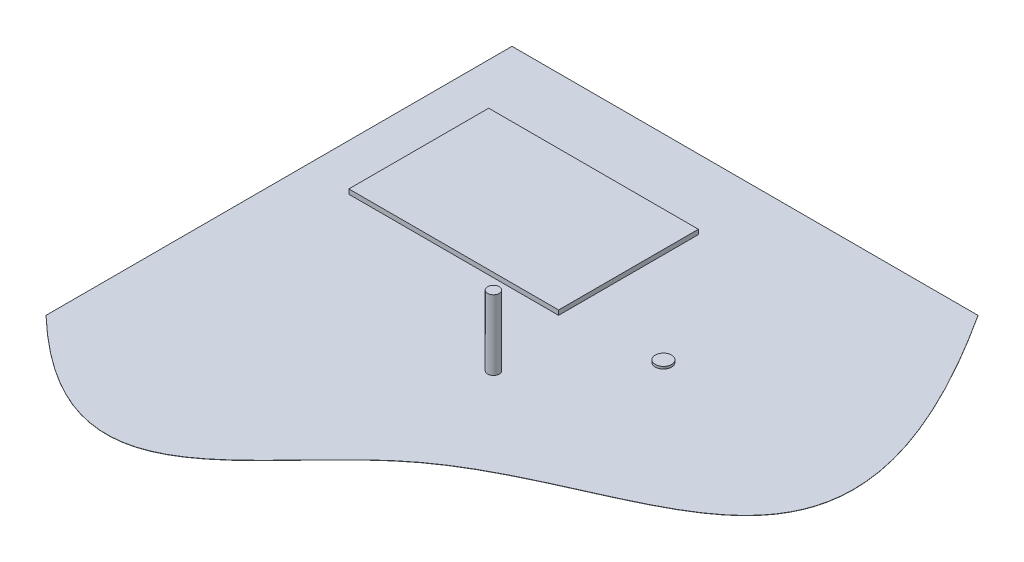
SolidWorks part; units mm, degrees
ref_plane "Спереди" through (0, 0, 0) normal (0, 0, 1) x (1, 0, 0)
ref_plane "Сверху" through (0, 0, 0) normal (0, 1, 0) x (1, 0, 0)
ref_plane "Справа" through (0, 0, 0) normal (1, 0, 0) x (0, 0, -1)
sketch "Эскиз1" plane through (0, 0, 0) normal (0, 1, 0) x (1, 0, 0)
  line L0 (0, 0) -> (20000, 0)
  line L1 (0, 0) -> (0, -20000)
  spline S0 degree 3 poles (0, -20000) (7198.3528, -26864.5196) (12070.5058, -12028.819) (29348.4021, -14440.6963) (20000, 0) knots 0 0 0 0 0.41356 1 1 1 1
  point P5 (8873.6019, -21813.3955)
  dimension "D1" = 20000
  dimension "D2" = 20000
extrude "Бобышка-Вытянуть1" add sketch "Эскиз1" along normal blind 10
sketch "Эскиз2" plane through (0, 10, 0) normal (0, 1, 0) x (1, 0, 0)
  line L0 (20000, 0) -> (0, 0) construction
  line L1 (2000, -3000) -> (11000, -3000)
  line L2 (2000, -3000) -> (2000, -9000)
  line L3 (2000, -9000) -> (11000, -9000)
  line L4 (11000, -3000) -> (11000, -9000)
  line L5 (0, 0) -> (0, -20000) construction
  dimension "D1" = 3000
  dimension "D2" = 2000
  dimension "D3" = 9000
  dimension "D4" = 6000
extrude "Бобышка-Вытянуть2" add sketch "Эскиз2" along normal blind 200
sketch "Эскиз3" plane through (0, 10, 0) normal (0, 1, 0) x (1, 0, 0)
  line L0 (11000, -9000) -> (11000, -3000) construction
  line L1 (2000, -9000) -> (11000, -9000) construction
  circle A0 centre (15000, -8500) radius 350
  point P4 (0, 0)
  dimension "D1" = 700
  dimension "D2" = 4000
  dimension "D3" = 500
extrude "Бобышка-Вытянуть3" add sketch "Эскиз3" along normal blind 100 separate body
sketch "Эскиз4" plane through (0, 10, 0) normal (0, 1, 0) x (1, 0, 0)
  circle A0 centre (11661.5897, -12457.6856) radius 250
  dimension "D1" = 500
extrude "Бобышка-Вытянуть4" add sketch "Эскиз4" along normal blind 3000 separate body
